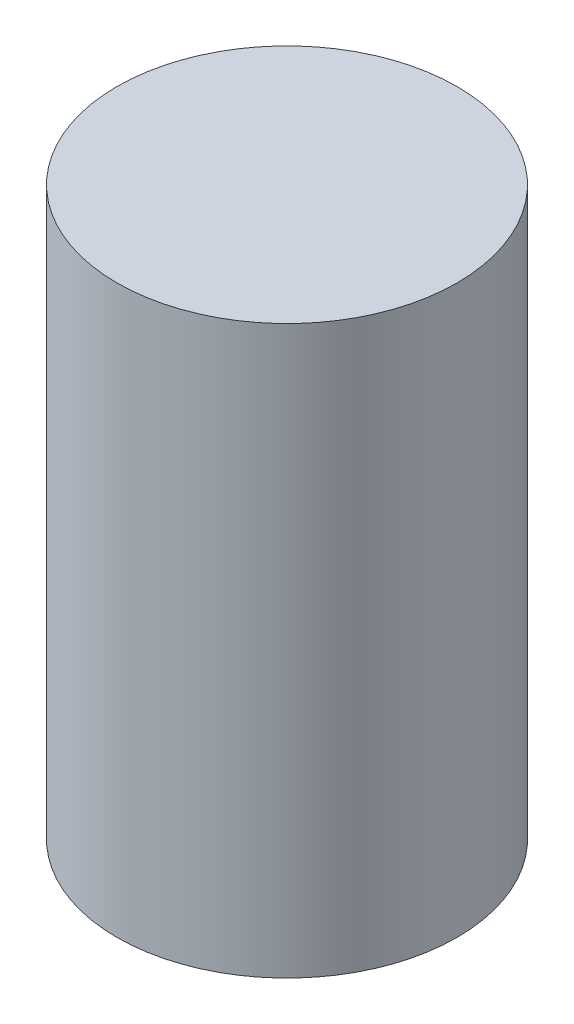
SolidWorks part; units mm, degrees
ref_plane "前视基准面" through (0, 0, 0) normal (0, 0, 1) x (1, 0, 0)
ref_plane "上视基准面" through (0, 0, 0) normal (0, 1, 0) x (1, 0, 0)
ref_plane "右视基准面" through (0, 0, 0) normal (1, 0, 0) x (0, 0, -1)
sketch "草图1" plane through (0, 0, 0) normal (0, 1, 0) x (1, 0, 0)
  circle A0 centre (-8.5222, 2.1145) radius 4.5
  dimension "D1" = 9
extrude "凸台-拉伸2" add sketch "草图1" along normal blind 15 contours A0
